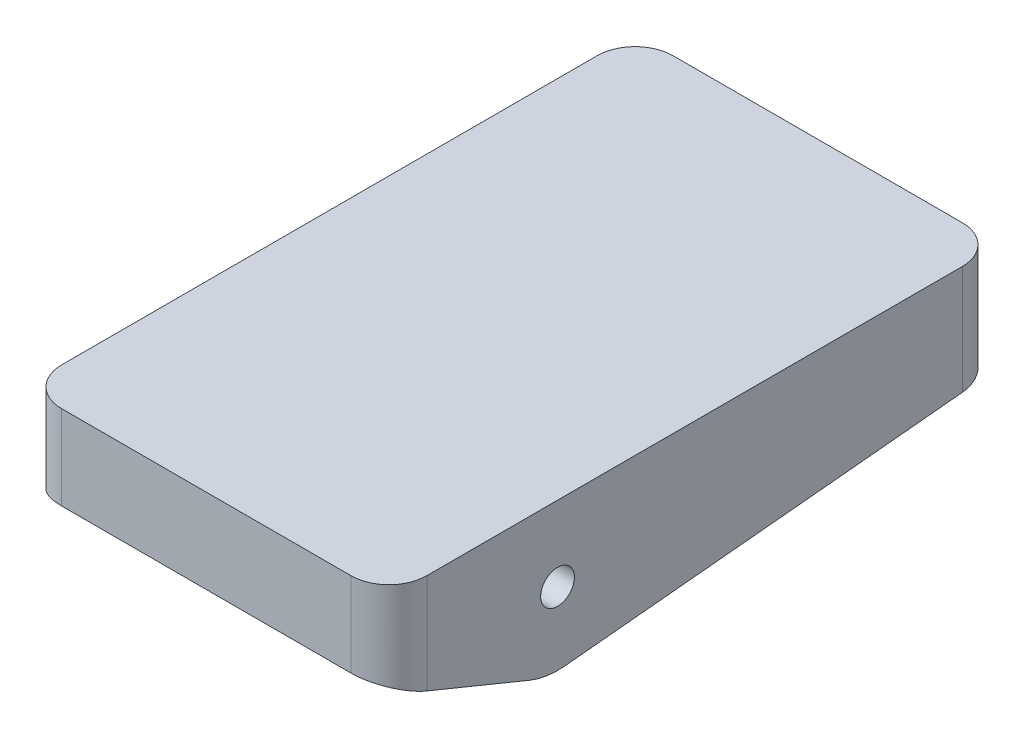
SolidWorks part; units mm, degrees
ref_plane "Front Plane" through (0, 0, 0) normal (0, 0, 1) x (1, 0, 0)
ref_plane "Top Plane" through (0, 0, 0) normal (0, 1, 0) x (1, 0, 0)
ref_plane "Right Plane" through (0, 0, 0) normal (1, 0, 0) x (0, 0, -1)
ref_plane "Plane1" through (0, 12.8, 0) normal (0, 1, 0) x (1, 0, 0)
sketch "GEOMETRY" plane through (0, 0, 0) normal (1, 0, 0) x (0, 0, -1)
  line L0 (0, 0) -> (0, 12.5) construction
  line L1 (0, 12.5) -> (105, 12.5) construction
  line L2 (0, 12.5) -> (-40, 12.5) construction
  circle A0 centre (0, 0) radius 12.5 construction
  dimension "D1" = 40
  dimension "D2" = 105
sketch "Sketch4" plane through (0, 12.8, 0) normal (0, 1, 0) x (1, 0, 0)
  line L0 (39, 9.1288) -> (39, 88.5257) construction
  line L1 (-39, 9.1288) -> (-39, 88.5257) construction
  line L2 (39, 9.1288) -> (39, 88.5257) construction
  line L3 (-39, 9.1288) -> (-39, 88.5257) construction
  line L4 (-43.3, 105) -> (43.3, 105)
  line L5 (-39.3, 101) -> (39.3, 101)
  line L6 (-39.3, 101) -> (-39.3, -36)
  line L7 (-39.3, -36) -> (39.3, -36)
  line L8 (39.3, 101) -> (39.3, -36)
  line L9 (43.3, 105) -> (43.3, -40)
  line L10 (-43.3, -40) -> (43.3, -40)
  line L11 (-43.3, 105) -> (-43.3, -40)
  dimension "D1" = 4
  dimension "D2" = 0.3
  dimension "D3" = 0.3
extrude "Boss-Extrude2" add sketch "Sketch4" against normal blind 30
sketch "Sketch5" plane through (0, 12.8, 0) normal (0, 1, 0) x (1, 0, 0)
  line L4 (-43.3, 105) -> (-43.3, -40)
  line L5 (-43.3, -40) -> (43.3, -40)
  line L6 (43.3, -40) -> (43.3, 105)
  line L7 (43.3, 105) -> (-43.3, 105)
  line L8 (-43.3, 105) -> (-43.3, -40)
  line L9 (-43.3, -40) -> (43.3, -40)
  line L10 (43.3, -40) -> (43.3, 105)
  line L11 (43.3, 105) -> (-43.3, 105)
  dimension "D1" = 0
extrude "Boss-Extrude3" add sketch "Sketch5" along normal blind 5
sketch "Sketch6" plane through (0, 0, 0) normal (1, 0, 0) x (0, 0, -1)
  line L0 (-40, -17.2) -> (105, -17.2) construction
  line L1 (-40, -2.2) -> (-6.5206, -15.9161)
  line L2 (-40, -17.2) -> (-40, 17.8) construction
  line L3 (1.6435, -17.1213) -> (105, -7.2)
  line L4 (105, -17.2) -> (105, 17.8) construction
  line L5 (-40, -2.2) -> (-40, -30)
  line L6 (-40, -30) -> (105, -30)
  line L7 (105, -30) -> (105, -7.2)
  arc A0 (-6.5206, -15.9161) -> (1.6435, -17.1213) centre (0, 0) ccw
  circle A1 centre (0, 0) radius 4
  dimension "D1" = 30
  dimension "D4" = 8
  dimension "D2" = 25
  dimension "D3" = 20
extrude "Cut-Extrude2" cut sketch "Sketch6" against normal mid plane 113
sketch "Sketch1" plane through (-39.3, 0, 0) normal (1, 0, 0) x (0, 0, -1)
  line L0 (-12.2958, 0.3204) -> (-27.3199, 12.8)
  line L2 (0, 0) -> (0, 12.8) construction
  line L3 (101, 12.8) -> (-36, 12.8) construction
  line L4 (-27.3199, 12.8) -> (97.7135, 12.8)
  line L5 (-36, 12.8) -> (101, 12.8) construction
  line L6 (11.8423, -3.3241) -> (97.7135, 12.8)
  arc A0 (-12.2958, 0.3204) -> (11.8423, -3.3241) centre (0, 0) ccw
  circle A1 centre (0, 0) radius 12.5 construction
  circle A2 centre (0, 0) radius 12.7 construction
  circle A3 centre (0, 0) radius 4
  circle A4 centre (0, 0) radius 12.3 construction
  point P7 (11.7625, 3.5962)
  dimension "D1" = 0.2
  dimension "D3" = 0.4
  dimension "D8" = 8
extrude "Boss-Extrude1" add sketch "Sketch1" along normal blind 5
mirror "Mirror1" about plane through (0, 0, 0) normal (1, 0, 0) of "Boss-Extrude1"
sketch "Sketch7" plane through (0, 12.8, 0) normal (0, -1, 0) x (1, 0, 0)
  line L0 (39.3, 36) -> (-39.3, 36) construction
  line L1 (-34.3, 36) -> (34.3, 36)
  line L2 (-34.3, 36) -> (-34.3, 20.25)
  line L3 (-34.3, -101) -> (34.3, -101)
  line L4 (34.3, 36) -> (34.3, 20.25)
  line L5 (-39.3, -101) -> (39.3, -101) construction
  line L6 (34.3, -11.8423) -> (34.3, -97.7135) construction
  line L7 (-34.3, -11.8423) -> (-34.3, -97.7135) construction
  line L8 (-34.3, 20.25) -> (34.3, 20.25)
  line L9 (-34.3, 17.25) -> (34.3, 17.25)
  line L10 (-34.3, -1.5) -> (34.3, -1.5)
  line L11 (-34.3, 1.5) -> (34.3, 1.5)
  line L12 (-34.3, -28.625) -> (34.3, -28.625)
  line L13 (-34.3, -23.625) -> (34.3, -23.625)
  line L14 (-34.3, -53.75) -> (34.3, -53.75)
  line L15 (-34.3, -50.75) -> (34.3, -50.75)
  line L16 (-34.3, -78.875) -> (34.3, -78.875)
  line L17 (-34.3, -75.875) -> (34.3, -75.875)
  line L18 (34.3, 17.25) -> (34.3, 1.5)
  line L19 (-34.3, 17.25) -> (-34.3, 1.5)
  line L20 (-34.3, -1.5) -> (-34.3, -23.625)
  line L21 (34.3, -1.5) -> (34.3, -23.625)
  line L22 (-34.3, -28.625) -> (-34.3, -50.75)
  line L23 (34.3, -28.625) -> (34.3, -50.75)
  line L24 (-34.3, -53.75) -> (-34.3, -75.875)
  line L25 (34.3, -53.75) -> (34.3, -75.875)
  line L26 (-34.3, -78.875) -> (-34.3, -101)
  line L27 (34.3, -78.875) -> (34.3, -101)
  line L28 (-43.3, 0) -> (43.3, 0) construction
  line L30 (43.3, -105) -> (43.3, -1.6435) construction
  line L31 (0, 1.5) -> (0, -1.5) construction
  point P35 (0, 0)
  dimension "D2" = 3
  dimension "D3" = 3
  dimension "D4" = 5
  dimension "D6" = 3
  dimension "D7" = 3
extrude "Cut-Extrude3" cut sketch "Sketch7" against normal blind 2.5
fillet "Fillet1" radius 9 4 edges at (-43.3, 7.8, 40) (-43.3, 5.3, -105) (43.3, 5.3, -105) (43.3, 7.8, 40)
sketch "Sketch12" plane through (0, 12.8, 0) normal (0, -1, 0) x (1, 0, 0)
  line L0 (-34.3, 1.5) -> (34.3, 1.5) construction
  line L4 (34.3, 1.5) -> (-34.3, 1.5)
  line L5 (-34.3, 1.5) -> (-34.3, -1.5)
  line L6 (-34.3, -1.5) -> (34.3, -1.5)
  line L7 (34.3, -1.5) -> (34.3, 1.5)
  line L8 (28.8, 1.5) -> (-28.8, 1.5)
  line L9 (-28.8, 1.5) -> (-28.8, -1.5)
  line L10 (-28.8, -1.5) -> (28.8, -1.5)
  line L11 (28.8, -1.5) -> (28.8, 1.5)
  point P9 (0, 1.5)
  point P11 (0, 1.5)
  dimension "D2" = 57.6
  dimension "D3" = 3
  dimension "D1" = 0
extrude "Boss-Extrude6" add sketch "Sketch12" along normal blind 8.5
sketch "Sketch13" plane through (0, 0, -1.5) normal (0, 0, -1) x (-1, 0, 0)
  line L0 (-28.8, 4.3) -> (-28.8, 12.8) construction
  line L1 (-28.8, 4.3) -> (-23.8, 4.3)
  line L2 (-28.8, 4.3) -> (-28.8, 6.8)
  line L3 (-28.8, 6.8) -> (-23.8, 6.8)
  line L4 (-23.8, 4.3) -> (-23.8, 6.8)
  line L5 (28.8, 4.3) -> (23.8, 4.3)
  line L6 (28.8, 4.3) -> (28.8, 6.8)
  line L7 (28.8, 6.8) -> (23.8, 6.8)
  line L8 (23.8, 4.3) -> (23.8, 6.8)
  line L9 (28.8, 4.3) -> (-28.8, 4.3) construction
  point P10 (-28.8, 4.3)
  point P15 (28.8, 4.3)
  dimension "D1" = 5
  dimension "D2" = 2.5
extrude "Cut-Extrude4" cut sketch "Sketch13" against normal blind 5
fillet "Fillet6" radius 1 2 edges at (-23.8, 4.3, 0) (23.8, 4.3, 0)
fillet "Fillet2" radius 2 23 edges at (34.3, 14.05, -78.875) (34.3, 14.05, -53.75) (34.3, 14.05, -28.625) (34.3, 14.05, -1.5) (34.3, 14.05, 17.25) (-34.3, 14.05, -78.875) (-34.3, 14.05, -53.75) (-34.3, 14.05, -28.625) (-34.3, 14.05, -1.5) (-34.3, 14.05, 17.25) (-34.3, 14.05, 36) (34.3, 14.05, 36) (34.3, 14.05, 20.25) (34.3, 14.05, 1.5) (34.3, 14.05, -23.625) (34.3, 14.05, -75.875) (34.3, 14.05, -101) (-34.3, 14.05, -101) (-34.3, 14.05, -75.875) (-34.3, 14.05, -50.75) (-34.3, 14.05, -23.625) (-34.3, 14.05, 1.5) (-34.3, 14.05, 20.25)
fillet "Fillet3" radius 5 4 edges at (-39.3, 4.4806, 36) (-39.3, 2.608, -101) (39.3, 2.608, -101) (39.3, 4.4806, 36)
ref_plane "Plane2" through (-8, 0, 0) normal (1, 0, 0) x (0, 0, -1)
sketch "Sketch8" plane through (-8, 0, 0) normal (1, 0, 0) x (0, 0, -1)
  line L0 (0, 0) -> (87, 0) construction
  line L1 (87, 0) -> (87, 12) construction
  dimension "D2" = 12
  dimension "D3" = 87
sketch "Sketch10" plane through (0, 15.3, 0) normal (0, -1, 0) x (1, 0, 0)
  line L0 (32.3, 36) -> (-32.3, 36) construction
  line L1 (-34.3, 34) -> (-34.3, 22.25) construction
  circle A0 centre (-22.3, 24) radius 3
  dimension "D3" = 6
  dimension "D1" = 12
  dimension "D2" = 12
extrude "Boss-Extrude4" add sketch "Sketch10" along normal blind 2.5
fillet "Fillet4" radius 0.5 1 edges at (-22.3, 12.8, 21)
sketch "Sketch11" plane through (0, 12.8, 0) normal (0, -1, 0) x (1, 0, 0)
  line L8 (-29.3, -23.625) -> (-32.3, -23.625)
  line L10 (-29.3, -23.625) -> (-29.3, -28.625)
  line L12 (32.3, -23.625) -> (-32.3, -23.625)
  line L13 (-34.3, -21.625) -> (-34.3, -30.625)
  line L14 (-32.3, -28.625) -> (32.3, -28.625)
  line L15 (34.3, -30.625) -> (34.3, -21.625)
  line L16 (32.3, -23.625) -> (29.3, -23.625)
  line L17 (-34.3, -21.625) -> (-34.3, -30.625)
  line L18 (-32.3, -28.625) -> (-29.3, -28.625)
  line L19 (34.3, -30.625) -> (34.3, -21.625)
  line L20 (-24.3, -23.625) -> (-24.3, -28.625)
  line L22 (24.3, -23.625) -> (24.3, -28.625)
  line L24 (29.3, -23.625) -> (29.3, -28.625)
  line L25 (-24.3, -28.625) -> (24.3, -28.625)
  line L26 (24.3, -23.625) -> (-24.3, -23.625)
  line L27 (29.3, -28.625) -> (32.3, -28.625)
  arc A4 (-34.3, -21.625) -> (-32.3, -23.625) centre (-32.3, -21.625) ccw
  arc A5 (-32.3, -28.625) -> (-34.3, -30.625) centre (-32.3, -30.625) ccw
  arc A6 (34.3, -30.625) -> (32.3, -28.625) centre (32.3, -30.625) ccw
  arc A7 (32.3, -23.625) -> (34.3, -21.625) centre (32.3, -21.625) ccw
  arc A8 (-34.3, -21.625) -> (-32.3, -23.625) centre (-32.3, -21.625) ccw
  arc A9 (-32.3, -28.625) -> (-34.3, -30.625) centre (-32.3, -30.625) ccw
  arc A10 (34.3, -30.625) -> (32.3, -28.625) centre (32.3, -30.625) ccw
  arc A11 (32.3, -23.625) -> (34.3, -21.625) centre (32.3, -21.625) ccw
  dimension "D1" = 0
  dimension "D2" = 5
  dimension "D3" = 5
  dimension "D4" = 5
extrude "Boss-Extrude5" add sketch "Sketch11" along normal mid plane 1.5
fillet "Fillet5" radius 1 4 edges at (26.8, 12.8, -23.625) (26.8, 12.8, -28.625) (-26.8, 12.8, -23.625) (-26.8, 12.8, -28.625)
